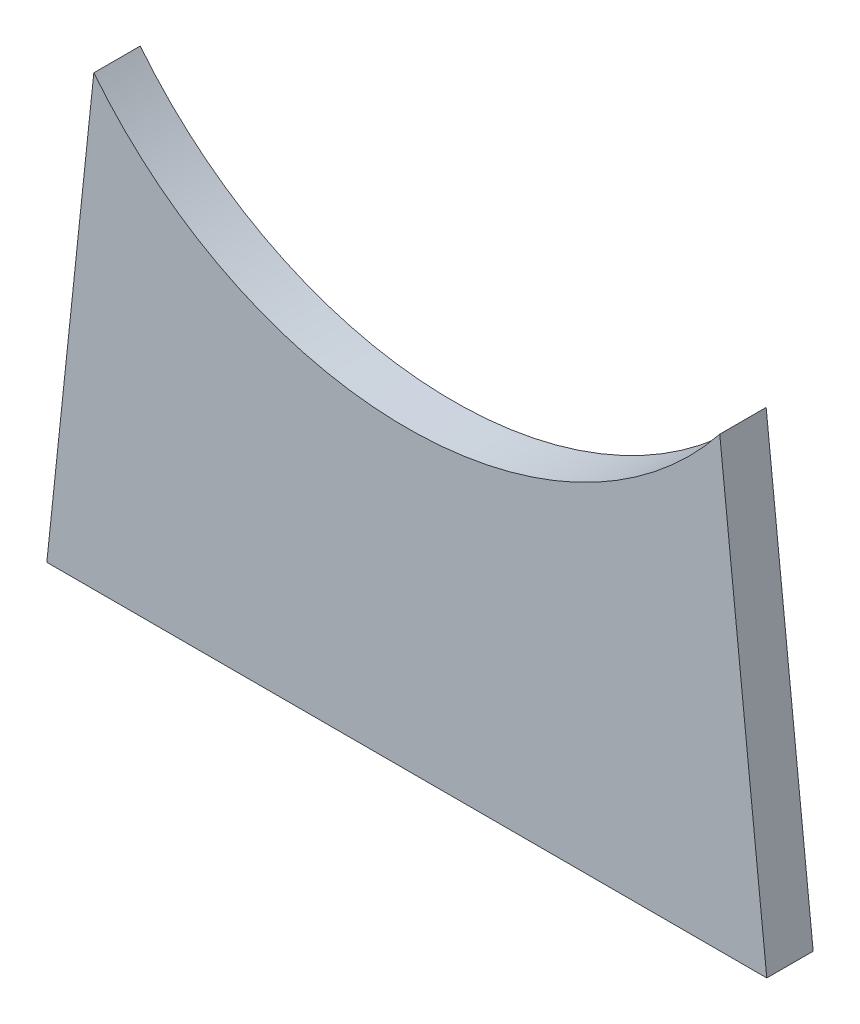
SolidWorks part; units mm, degrees
ref_plane "Front Plane" through (0, 0, 0) normal (0, 0, 1) x (1, 0, 0)
ref_plane "Top Plane" through (0, 0, 0) normal (0, 1, 0) x (1, 0, 0)
ref_plane "Right Plane" through (0, 0, 0) normal (1, 0, 0) x (0, 0, -1)
sketch "Sketch1" plane through (0, 0, 0) normal (0, 0, 1) x (1, 0, 0)
  line L0 (0, 0) -> (0, 3824.4466) construction
  line L1 (-1978.1275, 0) -> (1978.1275, 0)
  line L2 (1978.1275, 0) -> (1719.7025, 2458.75)
  line L3 (-1978.1275, 0) -> (-1719.7025, 2458.75)
  arc A0 (-1719.7025, 2458.75) -> (1719.7025, 2458.75) centre (0, 3824.4466) ccw
  dimension "D3" = 2458.75
  dimension "D4" = 2196.02
  dimension "D1" = 84
  dimension "D2" = 3956.255
extrude "Boss-Extrude1" add sketch "Sketch1" along normal mid plane 255
